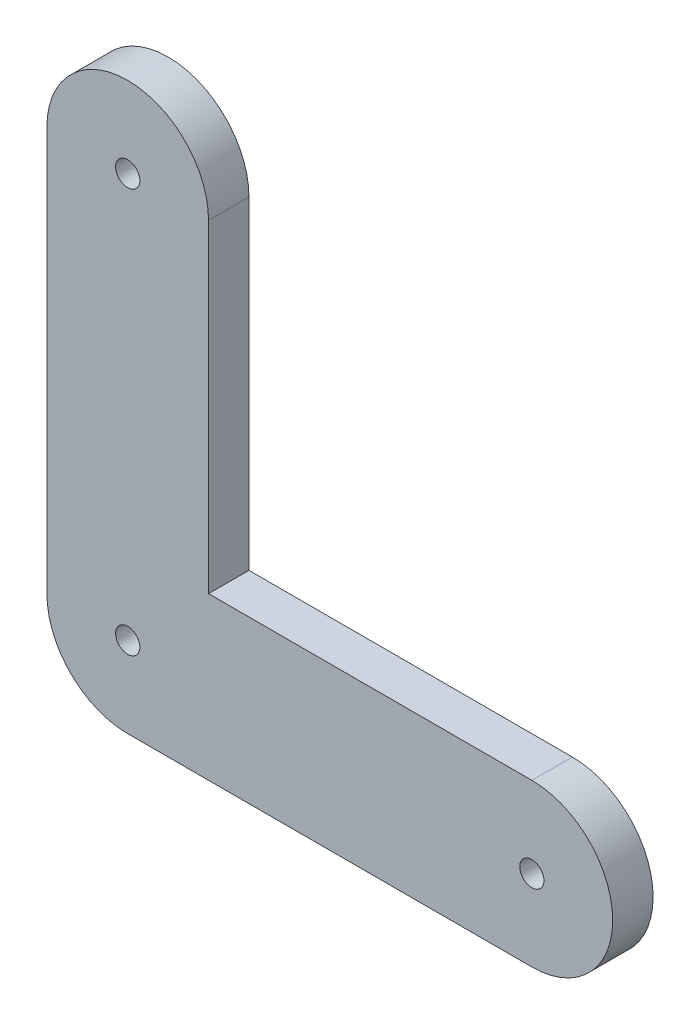
SolidWorks part; units mm, degrees
material "PVC 0.007 Plasticized"
ref_plane "Front Plane" through (0, 0, 0) normal (0, 0, 1) x (1, 0, 0)
ref_plane "Top Plane" through (0, 0, 0) normal (0, 1, 0) x (1, 0, 0)
ref_plane "Right Plane" through (0, 0, 0) normal (1, 0, 0) x (0, 0, -1)
sketch "Sketch1" plane through (0, 0, 0) normal (0, 0, 1) x (1, 0, 0)
  line L0 (0, 0) -> (50, 0)
  line L1 (0, 0) -> (0, 50)
  dimension "D1" = 50
  dimension "D2" = 50
sketch "Sketch2" plane through (0, 0, 0) normal (0, 0, 1) x (1, 0, 0)
  line L0 (-10, 50) -> (-10, 0)
  line L1 (0, -10) -> (50, -10)
  line L2 (10, 10) -> (50, 10)
  line L3 (10, 50) -> (10, 10)
  arc A0 (10, 50) -> (-10, 50) centre (0, 50) ccw
  arc A1 (-10, 0) -> (0, -10) centre (0, 0) ccw
  arc A2 (50, -10) -> (50, 10) centre (50, 0) ccw
  circle A3 centre (0, 0) radius 1.5
  circle A4 centre (0, 50) radius 1.5
  circle A5 centre (50, 0) radius 1.5
  dimension "D1" = 20
  dimension "D2" = 20
  dimension "D3" = 20
  dimension "D4" = 3
  dimension "D5" = 3
  dimension "D6" = 3
extrude "Boss-Extrude1" add sketch "Sketch2" along normal blind 5
